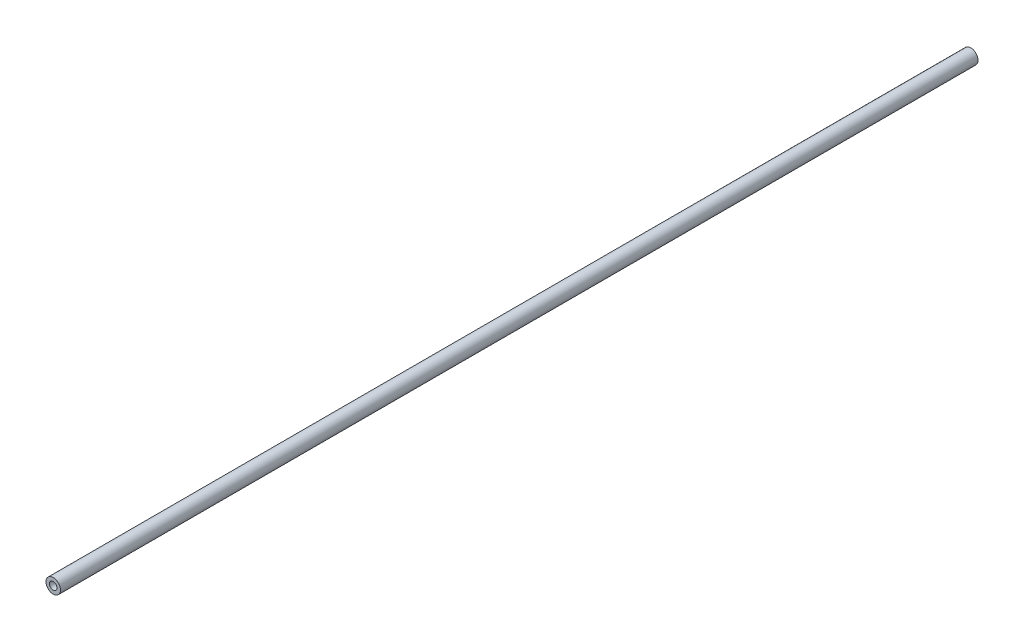
SolidWorks part; units mm, degrees
material "6061-T6 (SS)"
ref_plane "Front Plane" through (0, 0, 0) normal (0, 0, 1) x (1, 0, 0)
ref_plane "Top Plane" through (0, 0, 0) normal (0, 1, 0) x (1, 0, 0)
ref_plane "Right Plane" through (0, 0, 0) normal (1, 0, 0) x (0, 0, -1)
sketch "Sketch1" plane through (0, 0, 0) normal (0, 0, 1) x (1, 0, 0)
  circle A0 centre (0, 0) radius 2.4892
  circle A1 centre (0, 0) radius 4.7625
  dimension "D1" = 4.9784
  dimension "D2" = 9.525
extrude "Boss-Extrude1" add sketch "Sketch1" along normal mid plane 604.3625
